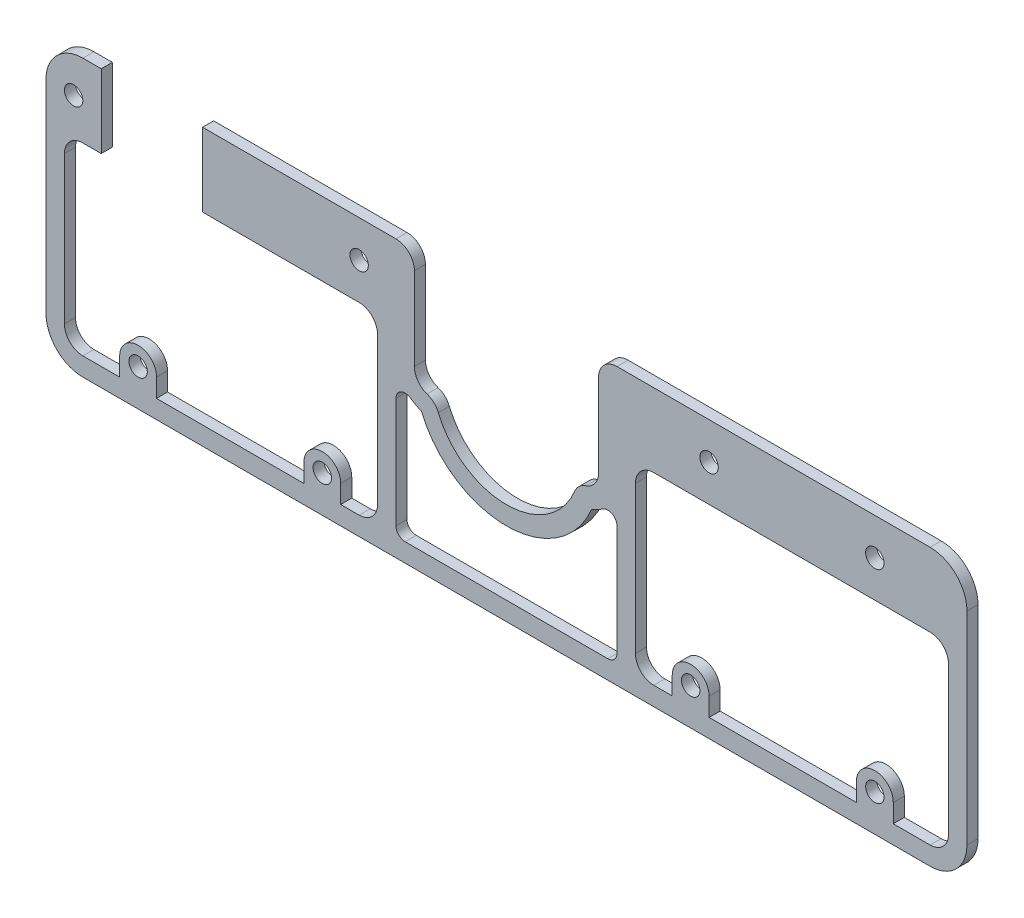
SolidWorks part; units mm, degrees
ref_plane "Front Plane" through (0, 0, 0) normal (0, 0, 1) x (1, 0, 0)
ref_plane "Top Plane" through (0, 0, 0) normal (0, 1, 0) x (1, 0, 0)
ref_plane "Right Plane" through (0, 0, 0) normal (1, 0, 0) x (0, 0, -1)
sketch "Sketch1" plane through (0, 0, 0) normal (0, 0, 1) x (1, 0, 0)
  line L0 (-40, 20) -> (-40, 55) construction
  line L4 (-250, -55) -> (-250, 3.1783)
  line L8 (-50, 75) -> (-230, 75) construction
  line L17 (0, -20) -> (0, -40)
  line L25 (0, -65) -> (0, -75)
  line L26 (0, 75) -> (0, -75) construction
  line L27 (-50, 95) -> (50, 95) construction
  line L34 (0, -75) -> (-230, -75)
  line L156 (-50, 75) -> (-230, 75) construction
  line L161 (0, -40) -> (0, -65)
  line L165 (-164.3309, 75) -> (-60, 75)
  line L167 (-230, 75) -> (-220, 75)
  line L171 (-250, 3.1783) -> (-250, 55)
  line L172 (-220, 75) -> (-164.3309, 75)
  line L173 (-50, 65) -> (-50, 20)
  arc A0 (-40, 20) -> (0, -20) centre (0, 20) ccw construction
  circle A1 centre (0, 20) radius 30 construction
  arc A4 (-230, -75) -> (-250, -55) centre (-230, -55) cw
  arc A5 (-250, 55) -> (-230, 75) centre (-230, 55) cw
  arc A124 (0, -20) -> (-37, 4.8013) centre (0, 20) cw
  arc A125 (-60, 75) -> (-50, 65) centre (-60, 65) cw
  arc A126 (-43.125, 10.5008) -> (-50, 20) centre (-40, 20) cw
  arc A127 (-37, 4.8013) -> (-43.125, 10.5008) centre (-46.25, 1.0016) ccw
  point P0 (0, 0)
  point P10 (-50, 10)
  point P11 (0, 50)
  point P30 (-40, 75)
  point P45 (0, -30)
  point P74 (0, 95)
  dimension "D3" = 80
  dimension "D4" = 60
  dimension "D6" = 55
  dimension "D7" = 75
  dimension "D10" = 10
  dimension "D11" = 20
  dimension "D8" = 10
  dimension "D5" = 10
  dimension "D9" = 20
  dimension "D13" = 210
  dimension "D16" = 100
  dimension "D17" = 20
  dimension "D26" = 250
extrude "Boss-Extrude1" add sketch "Sketch1" along normal blind 6
mirror "Mirror1" about plane through (0, -20, 6) normal (-1, 0, 0) of "Boss-Extrude1"
sketch "Sketch4" plane through (0, 0, 6) normal (0, 0, 1) x (1, 0, 0)
  line L0 (-230, -75) -> (230, -75) construction
  line L1 (-70, 25.101) -> (-70, -54.899)
  line L2 (-50, 20) -> (-50, 65) construction
  line L7 (-240, -55) -> (-240, 25.101)
  line L8 (-250, 55) -> (-250, -55) construction
  line L11 (-110, 35.101) -> (-80, 35.101)
  line L12 (-110, 35.101) -> (-140, 35.101)
  line L13 (-230, 35.101) -> (-140, 35.101)
  line L15 (-230, -65) -> (-210, -65)
  line L16 (-210, -65) -> (-210, -55)
  line L17 (-190, -55) -> (-190, -65)
  line L18 (-190, -65) -> (-110, -65)
  line L19 (-110, -65) -> (-110, -55)
  line L20 (-90, -55) -> (-90, -64.899)
  line L21 (-90, -64.899) -> (-80, -64.899)
  circle A1 centre (-200, -55) radius 5
  circle A2 centre (-100, -55) radius 5
  arc A6 (-230, -65) -> (-240, -55) centre (-230, -55) cw
  arc A12 (-210, -55) -> (-190, -55) centre (-200, -55) cw
  arc A13 (-110, -55) -> (-90, -55) centre (-100, -55) cw
  arc A14 (-240, 25.101) -> (-230, 35.101) centre (-230, 25.101) cw
  arc A15 (-70, -54.899) -> (-80, -64.899) centre (-80, -54.899) cw
  arc A16 (-70, 25.101) -> (-80, 35.101) centre (-80, 25.101) ccw
  point P0 (0, -75)
  dimension "D13" = 10
  dimension "D17" = 10
  dimension "D2" = 10
  dimension "D3" = 200
  dimension "D4" = 100
  dimension "D7" = 20
  dimension "D9" = 10
  dimension "D11" = 20
  dimension "D16" = 80
extrude "Cut-Extrude2" cut sketch "Sketch4" against normal through all
mirror "Mirror2" about plane through (0, 0, 0) normal (1, 0, 0) of "Cut-Extrude2"
sketch "Sketch8" plane through (0, 0, 6) normal (0, 0, 1) x (1, 0, 0)
  line L0 (-60, 0) -> (-60, -64.899)
  line L2 (-60, -64.899) -> (60, -64.899)
  line L3 (60, -64.899) -> (60, 0)
  line L4 (-90, -64.899) -> (-80, -64.899) construction
  arc A0 (43.125, 10.5008) -> (50, 20) centre (40, 20) ccw construction
  arc A1 (43.125, 10.5008) -> (37, 4.8013) centre (46.25, 1.0016) ccw construction
  arc A2 (-37, 4.8013) -> (-43.125, 10.5008) centre (-46.25, 1.0016) ccw construction
  arc A3 (-50, 20) -> (-43.125, 10.5008) centre (-40, 20) ccw construction
  arc A4 (-37, 4.8013) -> (37, 4.8013) centre (0, 20) ccw construction
  arc A5 (43.125, 10.5008) -> (50, 20) centre (40, 20) ccw construction
  arc A6 (43.125, 10.5008) -> (37, 4.8013) centre (46.25, 1.0016) ccw construction
  arc A7 (-37, 4.8013) -> (-43.125, 10.5008) centre (-46.25, 1.0016) ccw construction
  arc A8 (-50, 20) -> (-43.125, 10.5008) centre (-40, 20) ccw construction
  arc A9 (-37, 4.8013) -> (37, 4.8013) centre (0, 20) ccw construction
  arc A10 (-52, 4) -> (-46.25, 1.0016) centre (-40, 20) ccw
  arc A11 (-46.25, 1.0016) -> (-46.25, 1.0016) centre (-46.25, 1.0016) ccw
  arc A12 (-46.25, 1.0016) -> (46.25, 1.0016) centre (0, 20) ccw
  arc A13 (46.25, 1.0016) -> (46.25, 1.0016) centre (46.25, 1.0016) ccw
  arc A14 (46.25, 1.0016) -> (52, 4) centre (40, 20) ccw
  arc A15 (46.25, 1.0016) -> (60, 20) centre (40, 20) ccw construction
  arc A16 (60, 0) -> (52, 4) centre (55, 0) ccw
  arc A17 (-60, 20) -> (-46.25, 1.0016) centre (-40, 20) ccw construction
  arc A18 (-60, 0) -> (-52, 4) centre (-55, 0) cw
  dimension "D2" = 5
  dimension "D1" = 10
extrude "Cut-Extrude5" cut sketch "Sketch8" against normal through all
fillet "Fillet5" radius 5 1 edges at (-60, -64.899, 3)
fillet "Fillet6" radius 5 1 edges at (60, -64.899, 3)
sketch "Sketch9" plane through (0, 0, 0) normal (0, 0, -1) x (-1, 0, 0)
  line L0 (-250, 55) -> (-250, -55) construction
  line L2 (250, 55) -> (250, -55) construction
  line L3 (165, 75) -> (165, 35.101)
  line L4 (60, 75) -> (230, 75) construction
  line L5 (230, 35.101) -> (80, 35.101) construction
  line L6 (165, 35.101) -> (220, 35.101)
  line L7 (220, 35.101) -> (220, 75)
  line L8 (220, 75) -> (165, 75)
  circle A0 centre (-200, 55) radius 5
  circle A1 centre (-110, 55) radius 5
  circle A2 centre (80, 55) radius 5
  circle A3 centre (235, 55) radius 5
  dimension "D1" = 10
  dimension "D3" = 90
  dimension "D4" = 15
  dimension "D5" = 170
  dimension "D7" = 20
  dimension "D2" = 50
  dimension "D6" = 55
  dimension "D8" = 30
extrude "Cut-Extrude6" cut sketch "Sketch9" against normal through all
